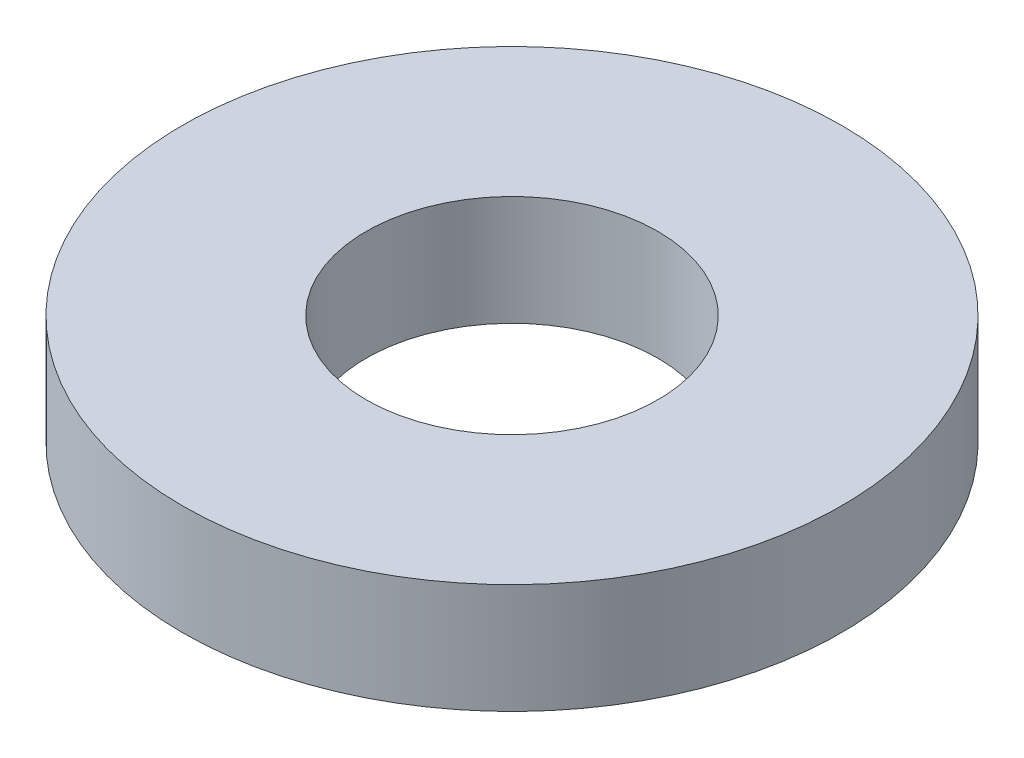
SolidWorks part; units mm, degrees
ref_plane "Front Plane" through (0, 0, 0) normal (0, 0, 1) x (1, 0, 0)
ref_plane "Top Plane" through (0, 0, 0) normal (0, 1, 0) x (1, 0, 0)
ref_plane "Right Plane" through (0, 0, 0) normal (1, 0, 0) x (0, 0, -1)
sketch "Sketch1" plane through (0, 0, 0) normal (0, 1, 0) x (1, 0, 0)
  circle A0 centre (0, 0) radius 2.1082
  circle A1 centre (0, 0) radius 4.7625
  dimension "D1" = 9.525
  dimension "D2" = 4.2164
extrude "Boss-Extrude1" add sketch "Sketch1" along normal blind 1.5875
